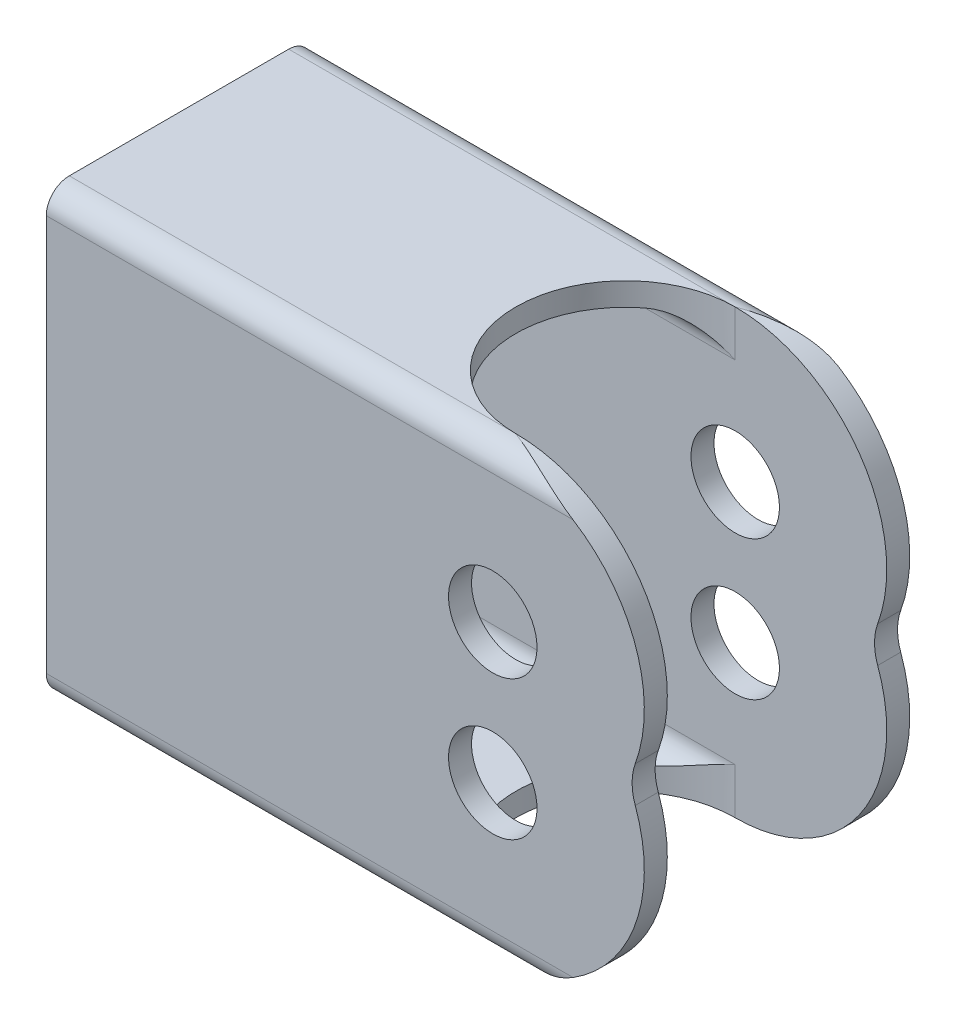
SolidWorks part; units mm, degrees
material "AISI 4130 Steel, annealed at 865C"
ref_plane "Front Plane" through (0, 0, 0) normal (0, 0, 1) x (1, 0, 0)
ref_plane "Top Plane" through (0, 0, 0) normal (0, 1, 0) x (1, 0, 0)
ref_plane "Right Plane" through (0, 0, 0) normal (1, 0, 0) x (0, 0, -1)
sketch "Sketch1" plane through (0, 0, 0) normal (0, 0, 1) x (1, 0, 0)
  line L0 (0, 0) -> (43.4742, 0)
other "Square tube 1.5X0.75-0.065 4130 TUBE(1)"
ref_plane "Plane1" through (0, 0, 0) normal (1, 0, 0) x (0, 1, 0)
sketch "Sketch2" plane through (0, 0, 0) normal (1, 0, 0) x (0, 1, 0)
  line L0 (-12.573, 7.874) -> (12.573, 7.874)
  line L1 (-14.224, -9.525) -> (14.224, -9.525)
  line L2 (-15.875, -7.874) -> (-15.875, 7.874)
  line L3 (-14.224, 9.525) -> (14.224, 9.525)
  line L4 (15.875, -7.874) -> (15.875, 7.874)
  line L5 (-15.875, -9.525) -> (15.875, 9.525) construction
  line L6 (-15.875, 9.525) -> (15.875, -9.525) construction
  line L7 (14.224, -6.223) -> (14.224, 6.223)
  line L8 (-12.573, -7.874) -> (12.573, -7.874)
  line L9 (-14.224, -6.223) -> (-14.224, 6.223)
  line L10 (-15.875, 9.525) -> (15.875, 9.525) construction
  line L11 (-15.875, -9.525) -> (-15.875, 9.525) construction
  line L12 (-15.875, -9.525) -> (15.875, -9.525) construction
  line L13 (15.875, -9.525) -> (15.875, 9.525) construction
  line L14 (-14.224, -7.874) -> (-14.224, 7.874) construction
  line L15 (-14.224, -7.874) -> (14.224, -7.874) construction
  line L16 (14.224, -7.874) -> (14.224, 7.874) construction
  line L17 (-14.224, 7.874) -> (14.224, 7.874) construction
  arc A0 (-14.224, 9.525) -> (-15.875, 7.874) centre (-14.224, 7.874) ccw
  arc A1 (-15.875, -7.874) -> (-14.224, -9.525) centre (-14.224, -7.874) ccw
  arc A2 (14.224, -9.525) -> (15.875, -7.874) centre (14.224, -7.874) ccw
  arc A3 (15.875, 7.874) -> (14.224, 9.525) centre (14.224, 7.874) ccw
  arc A4 (-14.224, -6.223) -> (-12.573, -7.874) centre (-12.573, -6.223) ccw
  arc A5 (12.573, -7.874) -> (14.224, -6.223) centre (12.573, -6.223) ccw
  arc A6 (14.224, 6.223) -> (12.573, 7.874) centre (12.573, 6.223) ccw
  arc A7 (-12.573, 7.874) -> (-14.224, 6.223) centre (-12.573, 6.223) ccw
  point P0 (0, 0)
  point P34 (0, 0)
  dimension "D4" = 1.651
  dimension "D5" = 1.651
  dimension "D6" = 1.651
  dimension "D1" = 19.05
  dimension "D2" = 31.75
  dimension "D3" = 1.651
sketch "Sketch3" plane through (0, 0, 9.525) normal (0, 0, 1) x (1, 0, 0)
  line L0 (43.4742, -15.875) -> (0, -15.875) construction
  line L1 (43.4742, -15.875) -> (32.0442, -15.875)
  line L2 (43.4742, 14.224) -> (43.4742, -14.224) construction
  line L3 (0, 0) -> (43.4742, 0) construction
  line L4 (0, 15.875) -> (0, 14.224)
  line L5 (0, 14.224) -> (43.4742, 14.224)
  line L6 (43.4742, 14.224) -> (43.4742, 15.875)
  line L7 (43.4742, 15.875) -> (0, 15.875)
  line L11 (43.4742, 15.875) -> (32.0442, 15.875)
  line L12 (43.4742, 15.875) -> (43.4742, -15.875)
  circle A0 centre (32.0442, 5) radius 3.175
  circle A1 centre (32.0442, -5) radius 3.175
  arc A2 (41.7016, 0) -> (32.0442, 15.875) centre (32.0442, 5) ccw
  arc A3 (32.0442, -15.875) -> (41.7016, 0) centre (32.0442, -5) ccw
  dimension "D5" = 6.35
  dimension "D2" = 11.43
  dimension "D3" = 5
  dimension "D4" = 5
  dimension "D1" = 0
extrude "Cut-Extrude1" cut sketch "Sketch3" against normal through all
sketch "Sketch4" plane through (0, 15.875, 0) normal (0, 1, 0) x (1, 0, 0)
  line L0 (28.8692, -9.525) -> (35.2192, -9.525) construction
  line L1 (28.8692, -9.525) -> (35.2192, -9.525) construction
  line L2 (39.849, -7.874) -> (0, -7.874) construction
  line L3 (39.849, 7.874) -> (0, 7.874) construction
  line L4 (39.849, -7.874) -> (32.0442, -7.874)
  line L5 (39.849, 7.874) -> (32.0442, 7.874)
  line L6 (39.849, 7.874) -> (39.849, -7.874)
  arc A0 (32.0442, 7.874) -> (32.0442, -7.874) centre (32.0442, 0) ccw
  point P8 (32.0442, -9.525)
extrude "Cut-Extrude2" cut sketch "Sketch4" against normal through all
fillet "Fillet1" radius 3.81 2 edges at (41.7016, 0, -8.6995) (41.7016, 0, 8.6995)
